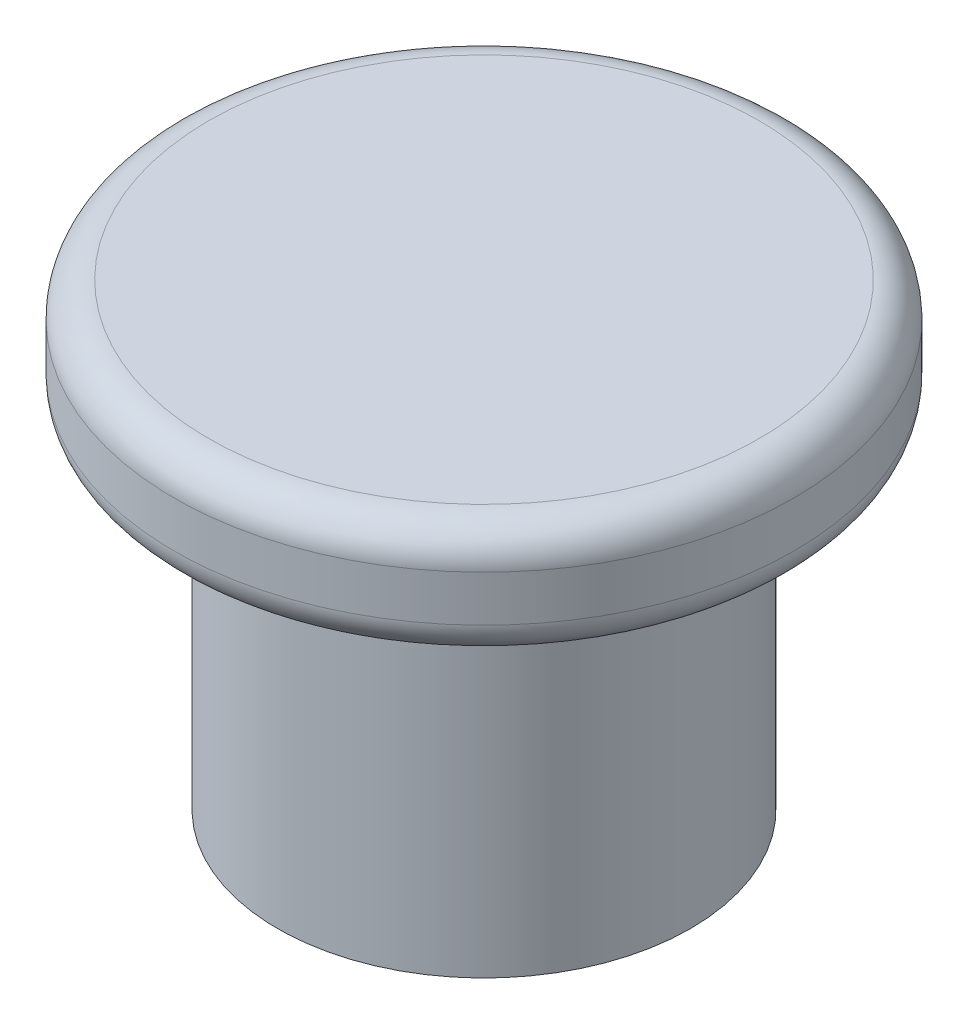
SolidWorks part; units mm, degrees
ref_plane "Front Plane" through (0, 0, 0) normal (0, 0, 1) x (1, 0, 0)
ref_plane "Top Plane" through (0, 0, 0) normal (0, 1, 0) x (1, 0, 0)
ref_plane "Right Plane" through (0, 0, 0) normal (1, 0, 0) x (0, 0, -1)
sketch "Sketch1" plane through (0, 0, 0) normal (0, 0, 1) x (1, 0, 0)
  line L0 (0, 20) -> (0, -20) construction
  line L1 (0, -20) -> (18, -20)
  line L2 (18, -20) -> (18, 10)
  line L3 (0, 20) -> (24, 20)
  line L4 (27, 17) -> (27, 13)
  line L5 (24, 10) -> (18, 10)
  line L6 (0, 20) -> (0, -20)
  arc A0 (27, 13) -> (24, 10) centre (24, 13) cw
  arc A1 (24, 20) -> (27, 17) centre (24, 17) cw
  point P3 (0, 0)
  point P12 (27, 20)
  dimension "D5" = 3
  dimension "D1" = 40
  dimension "D2" = 18
  dimension "D3" = 30
  dimension "D4" = 27
revolve "Revolve1" add sketch "Sketch1" angle 360 about L0
sketch "Sketch2" plane through (0, -20, 0) normal (0, -1, 0) x (1, 0, 0)
  circle A0 centre (0, 0) radius 14
  dimension "D1" = 28
extrude "Cut-Extrude1" cut sketch "Sketch2" against normal up to surface (30 mm away) up to face at (-24, 10, 0)
